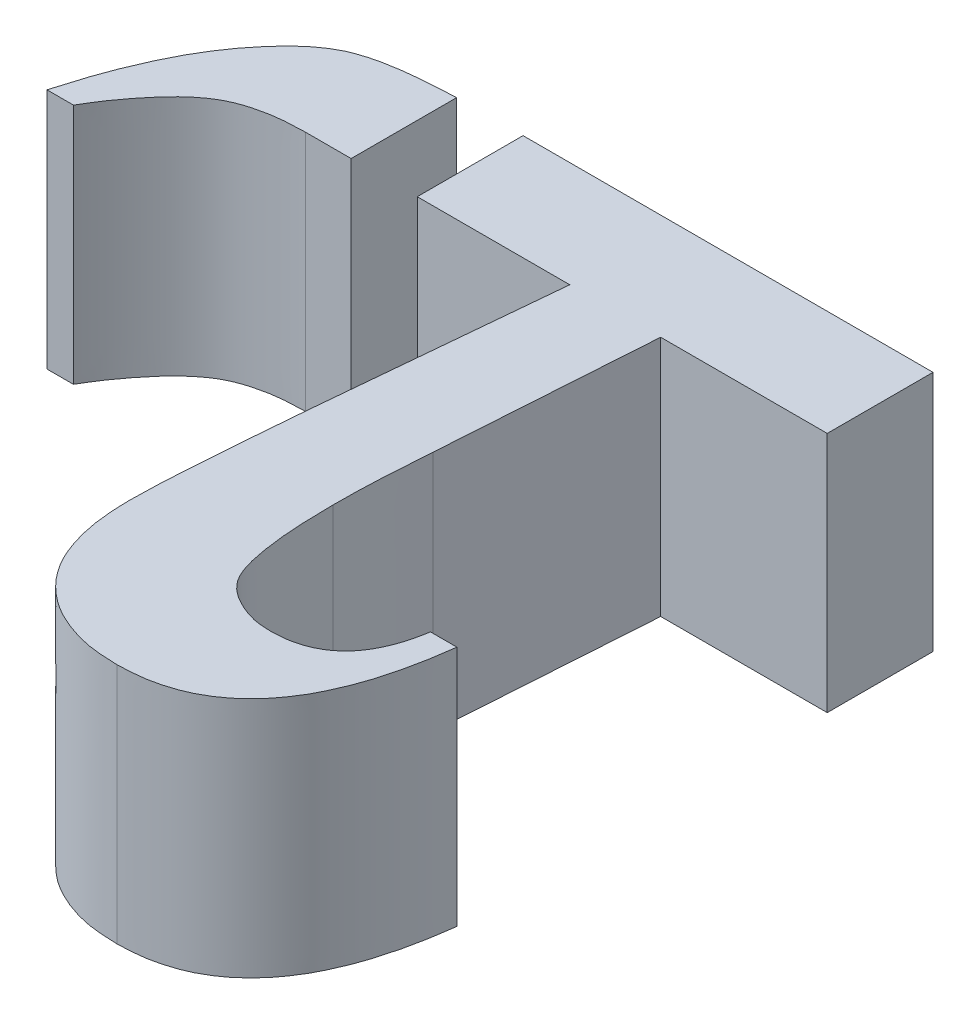
SolidWorks part; units mm, degrees
ref_plane "Front Plane" through (0, 0, 0) normal (0, 0, 1) x (1, 0, 0)
ref_plane "Top Plane" through (0, 0, 0) normal (0, 1, 0) x (1, 0, 0)
ref_plane "Right Plane" through (0, 0, 0) normal (1, 0, 0) x (0, 0, -1)
sketch "Sketch2" plane through (0, 0, 0) normal (0, 1, 0) x (1, 0, 0)
  line L0 (0, 0) -> (31.8, 0) construction
  text T0 "π" font "Times New Roman" height 50
extrude "Boss-Extrude1" add sketch "Sketch2" along normal blind 12.7
sketch "Sketch3" plane through (0, 12.7, 0) normal (0, 1, 0) x (1, 0, 0)
  line L0 (11.8056, 28.4722) -> (15.2778, 28.4722)
  line L2 (11.8056, 28.4722) -> (15.2778, 28.4722)
  line L3 (11.8056, 28.4722) -> (11.8056, 34.59)
  line L4 (11.8056, 34.59) -> (15.2778, 34.59)
  line L5 (15.2778, 28.4722) -> (15.2778, 34.59)
  line M2 (36.8056, 34.0278) -> (13.2921, 34.0278)
  spline M3 degree 3 poles (13.2921, 34.0278) (12.9268, 34.0254) (12.225, 34.021) (11.2113, 33.9939) (10.286, 33.9219) (9.4446, 33.8558) (8.696, 33.7434) (8.0271, 33.6193) (7.4491, 33.4555) (6.7726, 33.2249) (5.9967, 32.7859) (5.1185, 32.059) (4.2591, 31.116) (3.404, 29.9807) (2.6041, 28.6426) (1.8863, 27.1199) (1.2293, 25.4311) (0.8771, 24.2326) (0.6944, 23.6111) knots 0 0 0 0 0.060025 0.115321 0.166552 0.2125 0.253933 0.290879 0.324185 0.352567 0.408153 0.469409 0.53921 0.617298 0.702602 0.794837 0.89361 1 1 1 1
  spline M7 degree 3 poles (11.8056, 28.4722) (11.7481, 27.7376) (11.6371, 26.3176) (11.4106, 24.2683) (11.1948, 22.3666) (10.9266, 20.6249) (10.6667, 19.033) (10.3552, 17.603) (10.0526, 16.3164) (9.5835, 14.8145) (8.9128, 13.0516) (7.9241, 11.0191) (6.7785, 9.0096) (5.8809, 7.7333) (5.4253, 7.0855) knots 0 0 0 0 0.097498 0.188461 0.272819 0.350727 0.421621 0.486203 0.54436 0.596439 0.694303 0.793629 0.895262 1 1 1 1
  spline M8 degree 3 poles (5.4253, 7.0855) (5.13, 6.6718) (4.5879, 5.9124) (3.9752, 4.7856) (3.5617, 3.8003) (3.4998, 3.1676) (3.4722, 2.8863) knots 0 0 0 0 0.324491 0.595557 0.820162 1 1 1 1
  spline M9 degree 3 poles (3.4722, 2.8863) (3.4869, 2.6315) (3.5155, 2.1338) (3.7376, 1.428) (4.1059, 0.798) (4.6238, 0.2715) (5.2348, -0.159) (5.9273, -0.4698) (6.6815, -0.6565) (7.2074, -0.6816) (7.4761, -0.6944) knots 0 0 0 0 0.127152 0.248345 0.365828 0.488548 0.614409 0.737368 0.865811 1 1 1 1
  spline M10 degree 3 poles (7.4761, -0.6944) (7.8336, -0.6765) (8.5263, -0.6416) (9.5051, -0.2852) (10.3581, 0.2921) (10.958, 0.9642) (11.3788, 1.6424) (11.6867, 2.3016) (12.004, 3.0856) (12.3039, 4.0112) (12.5902, 5.0744) (12.8869, 6.2704) (13.1648, 7.603) (13.4365, 9.0867) (13.7156, 10.7451) (13.9545, 12.618) (14.2083, 14.7114) (14.4428, 17.0306) (14.6708, 19.5734) (14.8861, 22.3406) (15.0921, 25.3319) (15.2145, 27.4015) (15.2778, 28.4722) knots 0 0 0 0 0.033392 0.064699 0.096195 0.129076 0.148263 0.170853 0.197164 0.2275 0.261958 0.300352 0.342967 0.389507 0.441724 0.500547 0.566432 0.639355 0.718994 0.805699 0.899478 1 1 1 1
extrude "Cut-Extrude2" cut sketch "Sketch3" against normal blind 12.7 and the other way through all contours L0 M7 M8 M9 M10 | L0 L5 L3 M2 M3
